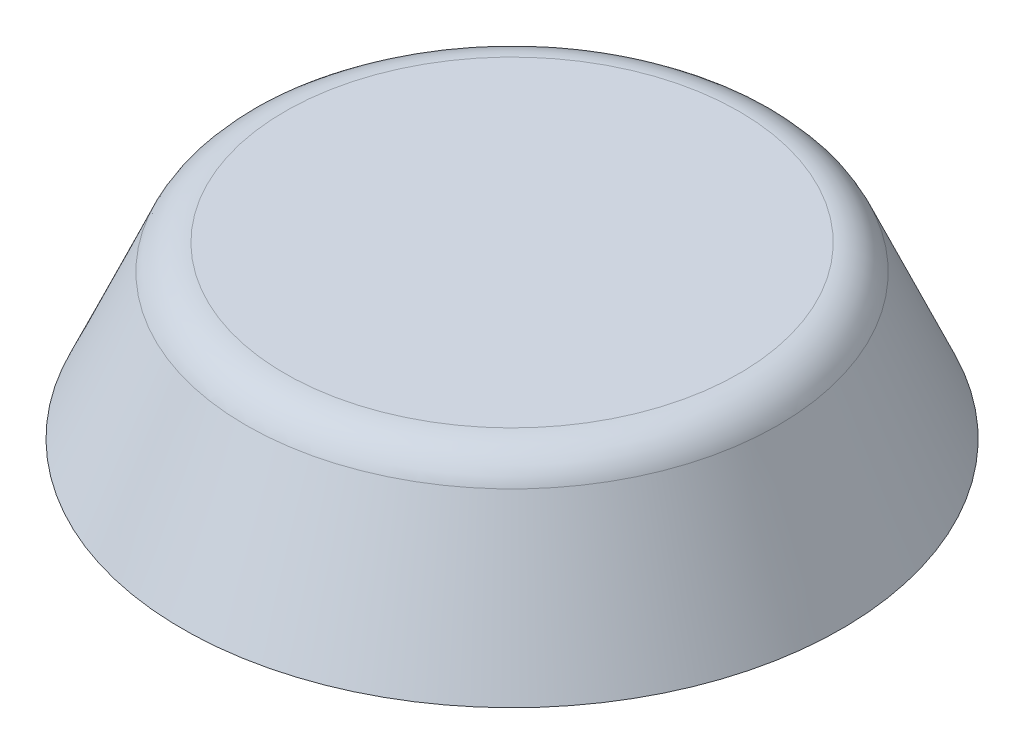
SolidWorks part; units mm, degrees
material "Rubber"
ref_plane "Front Plane" through (0, 0, 0) normal (0, 0, 1) x (1, 0, 0)
ref_plane "Top Plane" through (0, 0, 0) normal (0, 1, 0) x (1, 0, 0)
ref_plane "Right Plane" through (0, 0, 0) normal (1, 0, 0) x (0, 0, -1)
sketch "Sketch1" plane through (0, 0, 0) normal (0, 0, 1) x (1, 0, 0)
  line L0 (0, 0) -> (0, 3.175) construction
  line L1 (0, 0) -> (-6.1595, 0)
  line L2 (-6.1595, 0) -> (-4.7625, 3.175)
  line L3 (-4.7625, 3.175) -> (0, 3.175)
  line L4 (0, 0) -> (0, 3.175)
  dimension "D1" = 3.175
  dimension "D2" = 12.319
  dimension "D3" = 9.525
revolve "Revolve1" add sketch "Sketch1" angle 360 about L0
fillet "Fillet1" radius 0.7937 1 edges at (0, 3.175, -4.7625)
